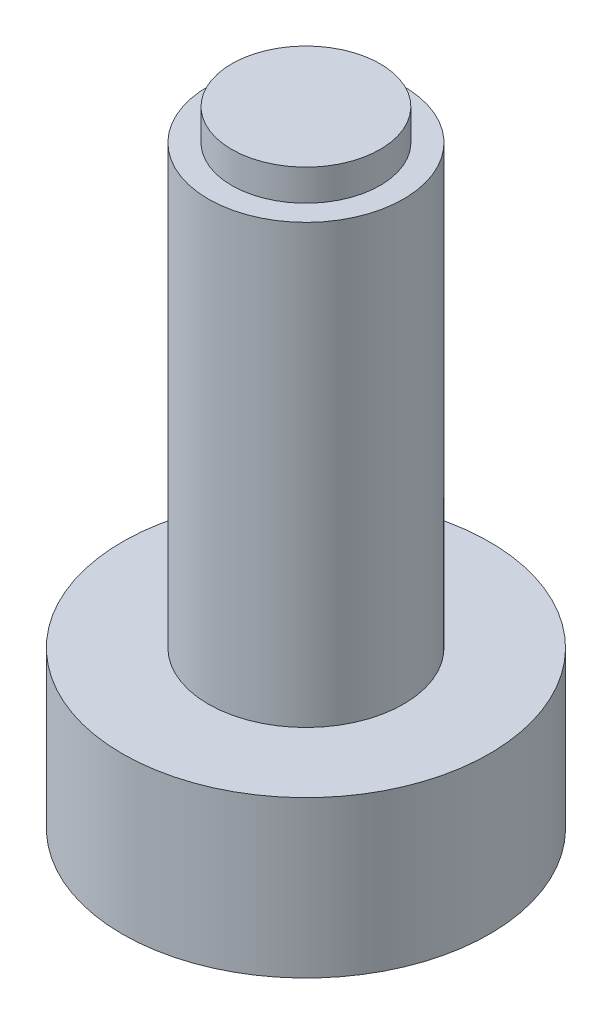
SolidWorks part; units mm, degrees
ref_plane "Front Plane" through (0, 0, 0) normal (0, 0, 1) x (1, 0, 0)
ref_plane "Top Plane" through (0, 0, 0) normal (0, 1, 0) x (1, 0, 0)
ref_plane "Right Plane" through (0, 0, 0) normal (1, 0, 0) x (0, 0, -1)
ref_plane "Plane1" through (0, -2, 0) normal (0, 1, 0) x (1, 0, 0)
sketch "Sketch1" plane through (0, -2, 0) normal (0, 1, 0) x (1, 0, 0)
  circle A0 centre (0, 0) radius 4.7
extrude "Boss-Extrude1" add sketch "Sketch1" along normal mid plane 4
ref_plane "Plane2" through (0, 5.6, 0) normal (0, 1, 0) x (1, 0, 0)
sketch "Sketch2" plane through (0, 5.6, 0) normal (0, 1, 0) x (1, 0, 0)
  circle A0 centre (0, 0) radius 2.5
extrude "Boss-Extrude2" add sketch "Sketch2" along normal mid plane 11.2
ref_plane "Plane3" through (0, 11.6, 0) normal (0, 1, 0) x (1, 0, 0)
sketch "Sketch3" plane through (0, 11.6, 0) normal (0, 1, 0) x (1, 0, 0)
  circle A0 centre (0, 0) radius 1.9
extrude "Boss-Extrude3" add sketch "Sketch3" along normal mid plane 0.8
ref_plane "Plane4" through (0, -2.75, 0) normal (0, 1, 0) x (1, 0, 0)
sketch "Sketch4" plane through (0, -2.75, 0) normal (0, 1, 0) x (1, 0, 0)
  line L0 (1.7321, 0) -> (0.866, -1.5)
  line L1 (0.866, -1.5) -> (-0.866, -1.5)
  line L2 (-0.866, -1.5) -> (-1.7321, 0)
  line L3 (-1.7321, 0) -> (-0.866, 1.5)
  line L4 (-0.866, 1.5) -> (0.866, 1.5)
  line L5 (0.866, 1.5) -> (1.7321, 0)
extrude "Cut-Extrude1" cut sketch "Sketch4" against normal mid plane 2.5
